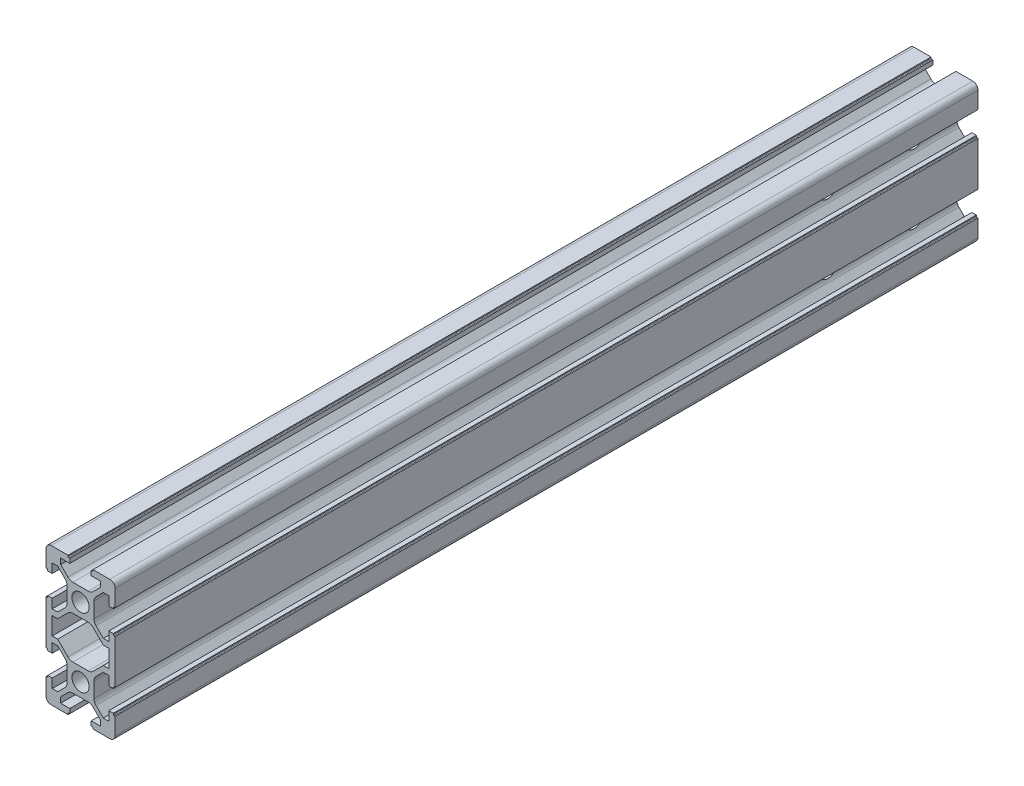
SolidWorks part; units mm, degrees
ref_plane "Alzado" through (0, 0, 0) normal (0, 0, 1) x (1, 0, 0)
ref_plane "Planta" through (0, 0, 0) normal (0, 1, 0) x (1, 0, 0)
ref_plane "Vista lateral" through (0, 0, 0) normal (1, 0, 0) x (0, 0, -1)
sketch "Croquis1" plane through (0, 0, 0) normal (0, 0, 1) x (1, 0, 0)
  line L0 (0, 0) -> (-10, -10) construction
  line L32 (0, 0) -> (-3.9, 0) construction
  line L58 (0, 0) -> (0, -3.9) construction
  line L60 (-4.4858, -3.6373) -> (-6.6, -5.7515)
  line L61 (-6.6, -5.7515) -> (-8.2, -5.7515)
  line L110 (-8.2, -5.7515) -> (-8.2, -3.1)
  line L111 (-8.2, -3.1) -> (-9.5, -3.1)
  line L112 (-9.5, -3.1) -> (-9.5, -3.4)
  line L113 (-9.7, -3.6) -> (-10, -3.6)
  line L114 (-10, -3.6) -> (-10, -8.5)
  line L115 (-3.6373, -4.4858) -> (-5.7515, -6.6)
  line L116 (-5.7515, -6.6) -> (-5.7515, -8.2)
  line L117 (-3.1, -8.2) -> (-3.1, -9.5)
  line L118 (-5.7515, -8.2) -> (-3.1, -8.2)
  line L119 (-3.1, -9.5) -> (-3.4, -9.5)
  line L120 (-3.6, -9.7) -> (-3.6, -10)
  line L121 (-3.6, -10) -> (-8.5, -10)
  line L122 (9.7, -3.6) -> (10, -3.6)
  line L123 (9.5, -3.1) -> (9.5, -3.4)
  line L124 (8.2, -3.1) -> (9.5, -3.1)
  line L125 (3.6, -10) -> (8.5, -10)
  line L126 (3.6, -9.7) -> (3.6, -10)
  line L127 (3.1, -9.5) -> (3.4, -9.5)
  line L128 (5.7515, -8.2) -> (3.1, -8.2)
  line L129 (3.1, -8.2) -> (3.1, -9.5)
  line L130 (5.7515, -6.6) -> (5.7515, -8.2)
  line L131 (3.6373, -4.4858) -> (5.7515, -6.6)
  line L132 (10, -3.6) -> (10, -8.5)
  line L133 (8.2, -5.7515) -> (8.2, -3.1)
  line L134 (6.6, -5.7515) -> (8.2, -5.7515)
  line L135 (4.4858, -3.6373) -> (6.6, -5.7515)
  line L136 (5.7515, 8.2) -> (3.1, 8.2)
  line L137 (3.6, 10) -> (8.5, 10)
  line L138 (-9.7, 3.6) -> (-10, 3.6)
  line L139 (-9.5, 3.1) -> (-9.5, 3.4)
  line L140 (-8.2, 3.1) -> (-9.5, 3.1)
  line L141 (-8.2, 5.7515) -> (-8.2, 3.1)
  line L142 (-6.6, 5.7515) -> (-8.2, 5.7515)
  line L143 (-4.4858, 3.6373) -> (-6.6, 5.7515)
  line L144 (3.1, 8.2) -> (3.1, 9.5)
  line L145 (3.1, 9.5) -> (3.4, 9.5)
  line L146 (3.6, 9.7) -> (3.6, 10)
  line L147 (-3.6, 10) -> (-8.5, 10)
  line L148 (-3.6, 9.7) -> (-3.6, 10)
  line L149 (-3.1, 9.5) -> (-3.4, 9.5)
  line L150 (-5.7515, 8.2) -> (-3.1, 8.2)
  line L151 (-3.1, 8.2) -> (-3.1, 9.5)
  line L152 (-5.7515, 6.6) -> (-5.7515, 8.2)
  line L153 (-3.6373, 4.4858) -> (-5.7515, 6.6)
  line L154 (-10, 3.6) -> (-10, 8.5)
  line L155 (4.4858, 3.6373) -> (6.6, 5.7515)
  line L156 (6.6, 5.7515) -> (8.2, 5.7515)
  line L157 (8.2, 5.7515) -> (8.2, 3.1)
  line L158 (10, 3.6) -> (10, 8.5)
  line L159 (3.6373, 4.4858) -> (5.7515, 6.6)
  line L160 (5.7515, 6.6) -> (5.7515, 8.2)
  line L161 (8.2, 3.1) -> (9.5, 3.1)
  line L162 (9.5, 3.1) -> (9.5, 3.4)
  line L163 (9.7, 3.6) -> (10, 3.6)
  line L164 (-3.9, 2.223) -> (-3.9, -2.223)
  line L165 (-2.223, -3.9) -> (2.223, -3.9)
  line L166 (3.9, -2.223) -> (3.9, 2.223)
  line L167 (2.223, 3.9) -> (-2.223, 3.9)
  circle A2 centre (0, 0) radius 2.5
  arc A3 (8.5, -10) -> (10, -8.5) centre (8.5, -8.5) ccw
  arc A4 (8.5, 10) -> (10, 8.5) centre (8.5, 8.5) cw
  arc A5 (-8.5, 10) -> (-10, 8.5) centre (-8.5, 8.5) ccw
  arc A6 (-10, -8.5) -> (-8.5, -10) centre (-8.5, -8.5) ccw
  arc A7 (-3.9, -2.223) -> (-4.4858, -3.6373) centre (-5.9, -2.223) cw
  arc A8 (4.4858, -3.6373) -> (3.9, -2.223) centre (5.9, -2.223) cw
  arc A9 (4.4858, 3.6373) -> (3.9, 2.223) centre (5.9, 2.223) ccw
  arc A10 (3.6373, 4.4858) -> (2.223, 3.9) centre (2.223, 5.9) cw
  arc A11 (-3.6373, 4.4858) -> (-2.223, 3.9) centre (-2.223, 5.9) ccw
  arc A12 (-4.4858, 3.6373) -> (-3.9, 2.223) centre (-5.9, 2.223) cw
  arc A13 (3.6373, -4.4858) -> (2.223, -3.9) centre (2.223, -5.9) ccw
  arc A14 (-3.6373, -4.4858) -> (-2.223, -3.9) centre (-2.223, -5.9) cw
  arc A15 (-3.4, -9.5) -> (-3.6, -9.7) centre (-3.4, -9.7) ccw
  arc A16 (3.6, -9.7) -> (3.4, -9.5) centre (3.4, -9.7) ccw
  arc A17 (9.7, -3.6) -> (9.5, -3.4) centre (9.7, -3.4) cw
  arc A18 (9.5, 3.4) -> (9.7, 3.6) centre (9.7, 3.4) cw
  arc A19 (3.4, 9.5) -> (3.6, 9.7) centre (3.4, 9.7) ccw
  arc A20 (-9.7, 3.6) -> (-9.5, 3.4) centre (-9.7, 3.4) cw
  arc A21 (-3.6, 9.7) -> (-3.4, 9.5) centre (-3.4, 9.7) ccw
  arc A22 (-9.5, -3.4) -> (-9.7, -3.6) centre (-9.7, -3.4) cw
  point P0 (0, 0)
  point P22 (10, -10)
  point P78 (10, 10)
  point P81 (-10, 10)
  point P90 (-3.9, -3.0515)
  point P93 (3.9, -3.0515)
  point P96 (3.9, 3.0515)
  point P99 (3.0515, 3.9)
  point P102 (-3.0515, 3.9)
  point P105 (-3.9, 3.0515)
  point P108 (3.0515, -3.9)
  point P111 (-3.0515, -3.9)
  point P116 (-3.6, -9.5)
  point P119 (3.6, -9.5)
  point P122 (9.5, -3.6)
  point P125 (9.5, 3.6)
  point P128 (3.6, 9.5)
  point P131 (-9.5, 3.6)
  point P134 (-3.6, 9.5)
  point P137 (-9.5, -3.6)
  dimension "D10" = 20
  dimension "D1" = 5
  dimension "D11" = 1.5
  dimension "D13" = 2
  dimension "D15" = 0.2
  dimension "D2" = 6.2
  dimension "D3" = 7.2
  dimension "D4" = 0.5
  dimension "D5" = 3.4
  dimension "D6" = 11.5029
  dimension "D7" = 6.1
  dimension "D8" = 1.8
  dimension "D9" = 1.2
extrude "Saliente-Extruir1" [suppressed] add sketch "Croquis1" along normal mid plane 100
sketch "Croquis3" plane through (0, 0, 0) normal (0, 0, 1) x (1, 0, 0)
  line L0 (-3.6363, -5.5152) -> (-6.6, -2.5556)
  line L3 (0, 0) -> (-10, 0) construction
  line L5 (-6.6, -2.5556) -> (-8.2, -2.5556)
  line L7 (0, -13.9) -> (0, -6.1) construction
  line L56 (-9.5, -13.1015) -> (-9.5, -13.4015)
  line L57 (-8.2, -13.1015) -> (-9.5, -13.1015)
  line L58 (-8.2, -15.7515) -> (-8.2, -13.1015)
  line L59 (-6.6, -15.7515) -> (-8.2, -15.7515)
  line L60 (-4.4858, -13.6373) -> (-6.6, -15.7515)
  line L61 (-3.9, -7.777) -> (-3.9, -12.223)
  line L62 (-6.6, -4.2515) -> (-4.4868, -6.3618)
  line L63 (-8.2, -4.2515) -> (-6.6, -4.2515)
  line L64 (-8.2, -6.9015) -> (-8.2, -4.2515)
  line L65 (-9.5, -6.9015) -> (-8.2, -6.9015)
  line L66 (-9.5, -6.6015) -> (-9.5, -6.9015)
  line L67 (-10, -6.4015) -> (-9.7, -6.4015)
  line L68 (-5.7515, -16.6) -> (-3.6373, -14.4858)
  line L69 (-5.7515, -18.2) -> (-5.7515, -16.6)
  line L70 (-3.1015, -18.2) -> (-5.7515, -18.2)
  line L71 (-3.1015, -19.5) -> (-3.1015, -18.2)
  line L72 (-3.4015, -19.5) -> (-3.1015, -19.5)
  line L73 (-3.6015, -20) -> (-3.6015, -19.7)
  line L74 (-8.5, -20) -> (-3.6015, -20)
  line L75 (-10, -13.6015) -> (-10, -18.5)
  line L76 (-9.7, -13.6015) -> (-10, -13.6015)
  line L102 (-10, -6.4015) -> (-10, 6.4015)
  line L103 (-8.2, -2.5556) -> (-8.2, 2.5556)
  line L104 (-2.223, -6.1) -> (2.223, -6.1)
  line L105 (-2.223, -13.9) -> (2.223, -13.9)
  line L106 (8.2, -2.5556) -> (8.2, 2.5556)
  line L107 (10, -6.4015) -> (10, 6.4015)
  line L108 (9.7, -13.6015) -> (10, -13.6015)
  line L109 (10, -13.6015) -> (10, -18.5)
  line L110 (8.5, -20) -> (3.6015, -20)
  line L111 (3.6015, -20) -> (3.6015, -19.7)
  line L112 (3.4015, -19.5) -> (3.1015, -19.5)
  line L113 (3.1015, -19.5) -> (3.1015, -18.2)
  line L114 (3.1015, -18.2) -> (5.7515, -18.2)
  line L115 (5.7515, -18.2) -> (5.7515, -16.6)
  line L116 (5.7515, -16.6) -> (3.6373, -14.4858)
  line L117 (10, -6.4015) -> (9.7, -6.4015)
  line L118 (9.5, -6.6015) -> (9.5, -6.9015)
  line L119 (9.5, -6.9015) -> (8.2, -6.9015)
  line L120 (8.2, -6.9015) -> (8.2, -4.2515)
  line L121 (8.2, -4.2515) -> (6.6, -4.2515)
  line L122 (6.6, -4.2515) -> (4.4868, -6.3618)
  line L123 (3.9, -7.777) -> (3.9, -12.223)
  line L124 (4.4858, -13.6373) -> (6.6, -15.7515)
  line L125 (6.6, -15.7515) -> (8.2, -15.7515)
  line L126 (8.2, -15.7515) -> (8.2, -13.1015)
  line L127 (8.2, -13.1015) -> (9.5, -13.1015)
  line L128 (9.5, -13.1015) -> (9.5, -13.4015)
  line L129 (6.6, -2.5556) -> (8.2, -2.5556)
  line L130 (3.6363, -5.5152) -> (6.6, -2.5556)
  line L131 (3.6363, 5.5152) -> (6.6, 2.5556)
  line L132 (6.6, 2.5556) -> (8.2, 2.5556)
  line L133 (9.5, 13.1015) -> (9.5, 13.4015)
  line L134 (8.2, 13.1015) -> (9.5, 13.1015)
  line L135 (8.2, 15.7515) -> (8.2, 13.1015)
  line L136 (6.6, 15.7515) -> (8.2, 15.7515)
  line L137 (4.4858, 13.6373) -> (6.6, 15.7515)
  line L138 (3.9, 7.777) -> (3.9, 12.223)
  line L139 (6.6, 4.2515) -> (4.4868, 6.3618)
  line L140 (8.2, 4.2515) -> (6.6, 4.2515)
  line L141 (8.2, 6.9015) -> (8.2, 4.2515)
  line L142 (9.5, 6.9015) -> (8.2, 6.9015)
  line L143 (9.5, 6.6015) -> (9.5, 6.9015)
  line L144 (10, 6.4015) -> (9.7, 6.4015)
  line L145 (5.7515, 16.6) -> (3.6373, 14.4858)
  line L146 (5.7515, 18.2) -> (5.7515, 16.6)
  line L147 (3.1015, 18.2) -> (5.7515, 18.2)
  line L148 (3.1015, 19.5) -> (3.1015, 18.2)
  line L149 (3.4015, 19.5) -> (3.1015, 19.5)
  line L150 (3.6015, 20) -> (3.6015, 19.7)
  line L151 (8.5, 20) -> (3.6015, 20)
  line L152 (10, 13.6015) -> (10, 18.5)
  line L153 (9.7, 13.6015) -> (10, 13.6015)
  line L154 (-2.223, 13.9) -> (2.223, 13.9)
  line L155 (-2.223, 6.1) -> (2.223, 6.1)
  line L156 (-9.7, 13.6015) -> (-10, 13.6015)
  line L157 (-10, 13.6015) -> (-10, 18.5)
  line L158 (-8.5, 20) -> (-3.6015, 20)
  line L159 (-3.6015, 20) -> (-3.6015, 19.7)
  line L160 (-3.4015, 19.5) -> (-3.1015, 19.5)
  line L161 (-3.1015, 19.5) -> (-3.1015, 18.2)
  line L162 (-3.1015, 18.2) -> (-5.7515, 18.2)
  line L163 (-5.7515, 18.2) -> (-5.7515, 16.6)
  line L164 (-5.7515, 16.6) -> (-3.6373, 14.4858)
  line L165 (-10, 6.4015) -> (-9.7, 6.4015)
  line L166 (-9.5, 6.6015) -> (-9.5, 6.9015)
  line L167 (-9.5, 6.9015) -> (-8.2, 6.9015)
  line L168 (-8.2, 6.9015) -> (-8.2, 4.2515)
  line L169 (-8.2, 4.2515) -> (-6.6, 4.2515)
  line L170 (-6.6, 4.2515) -> (-4.4868, 6.3618)
  line L171 (-3.9, 7.777) -> (-3.9, 12.223)
  line L172 (-4.4858, 13.6373) -> (-6.6, 15.7515)
  line L173 (-6.6, 15.7515) -> (-8.2, 15.7515)
  line L174 (-8.2, 15.7515) -> (-8.2, 13.1015)
  line L175 (-8.2, 13.1015) -> (-9.5, 13.1015)
  line L176 (-9.5, 13.1015) -> (-9.5, 13.4015)
  line L177 (-6.6, 2.5556) -> (-8.2, 2.5556)
  line L178 (-3.6363, 5.5152) -> (-6.6, 2.5556)
  line L179 (0, -10) -> (-9.5607, -19.5607) construction
  circle A8 centre (0, -10) radius 2.5
  arc A20 (-4.4858, -13.6373) -> (-3.9, -12.223) centre (-5.9, -12.223) ccw
  arc A21 (-3.9, -7.777) -> (-4.4868, -6.3618) centre (-5.9, -7.777) ccw
  arc A22 (-9.5, -6.6015) -> (-9.7, -6.4015) centre (-9.7, -6.6015) ccw
  arc A23 (-3.6363, -5.5152) -> (-2.223, -6.1) centre (-2.223, -4.1) ccw
  arc A24 (-2.223, -13.9) -> (-3.6373, -14.4858) centre (-2.223, -15.9) ccw
  arc A25 (-3.4015, -19.5) -> (-3.6015, -19.7) centre (-3.4015, -19.7) ccw
  arc A26 (-10, -18.5) -> (-8.5, -20) centre (-8.5, -18.5) ccw
  arc A27 (-9.7, -13.6015) -> (-9.5, -13.4015) centre (-9.7, -13.4015) ccw
  arc A34 (9.7, -13.6015) -> (9.5, -13.4015) centre (9.7, -13.4015) cw
  arc A35 (10, -18.5) -> (8.5, -20) centre (8.5, -18.5) cw
  arc A36 (3.4015, -19.5) -> (3.6015, -19.7) centre (3.4015, -19.7) cw
  arc A37 (2.223, -13.9) -> (3.6373, -14.4858) centre (2.223, -15.9) cw
  arc A38 (3.6363, -5.5152) -> (2.223, -6.1) centre (2.223, -4.1) cw
  arc A39 (9.5, -6.6015) -> (9.7, -6.4015) centre (9.7, -6.6015) cw
  arc A40 (3.9, -7.777) -> (4.4868, -6.3618) centre (5.9, -7.777) cw
  arc A41 (4.4858, -13.6373) -> (3.9, -12.223) centre (5.9, -12.223) cw
  arc A42 (4.4858, 13.6373) -> (3.9, 12.223) centre (5.9, 12.223) ccw
  arc A43 (3.9, 7.777) -> (4.4868, 6.3618) centre (5.9, 7.777) ccw
  arc A44 (9.5, 6.6015) -> (9.7, 6.4015) centre (9.7, 6.6015) ccw
  arc A45 (3.6363, 5.5152) -> (2.223, 6.1) centre (2.223, 4.1) ccw
  arc A46 (2.223, 13.9) -> (3.6373, 14.4858) centre (2.223, 15.9) ccw
  arc A47 (3.4015, 19.5) -> (3.6015, 19.7) centre (3.4015, 19.7) ccw
  arc A48 (10, 18.5) -> (8.5, 20) centre (8.5, 18.5) ccw
  arc A49 (9.7, 13.6015) -> (9.5, 13.4015) centre (9.7, 13.4015) ccw
  arc A50 (-9.7, 13.6015) -> (-9.5, 13.4015) centre (-9.7, 13.4015) cw
  arc A51 (-10, 18.5) -> (-8.5, 20) centre (-8.5, 18.5) cw
  arc A52 (-3.4015, 19.5) -> (-3.6015, 19.7) centre (-3.4015, 19.7) cw
  arc A53 (-2.223, 13.9) -> (-3.6373, 14.4858) centre (-2.223, 15.9) cw
  arc A54 (-3.6363, 5.5152) -> (-2.223, 6.1) centre (-2.223, 4.1) cw
  arc A55 (-9.5, 6.6015) -> (-9.7, 6.4015) centre (-9.7, 6.6015) cw
  arc A56 (-3.9, 7.777) -> (-4.4868, 6.3618) centre (-5.9, 7.777) cw
  arc A57 (-4.4858, 13.6373) -> (-3.9, 12.223) centre (-5.9, 12.223) cw
  circle A58 centre (0, 10) radius 2.5
  point P59 (8.2, 0)
  point P63 (8.2, 0)
  point P159 (10, 0)
  point P160 (-8.2, 0)
  point P174 (-8.2, 0)
  point P190 (-3.9, -10)
  point P193 (0, -10)
  dimension "D8" = 2
  dimension "D9" = 1.5
  dimension "D11" = 5
  dimension "D13" = 0.2
  dimension "D1" = 40
  dimension "D2" = 11.5
  dimension "D3" = 6.2
  dimension "D4" = 1.8
  dimension "D5" = 0.5
  dimension "D6" = 3.4
  dimension "D7" = 20
  dimension "D10" = 1.2
  dimension "D12" = 7.8
  dimension "D14" = 20
extrude "Saliente-Extruir3" add sketch "Croquis3" along normal mid plane 350 separate body
sketch "Sketch1" plane through (0, 20, 0) normal (0, 1, 0) x (1, 0, 0)
  line L0 (10, 175) -> (8.5, 175) construction
  line L1 (8.5, -175) -> (10, -175) construction
  line L2 (10, -175) -> (10, 175) construction
  line L3 (8.5, 175) -> (3.6015, 175) construction
  line L4 (3.6015, 175) -> (3.6015, -175) construction
  line L5 (3.6015, -175) -> (8.5, -175) construction
  line L6 (3.6373, 175) -> (2.223, 175) construction
  line L7 (2.223, -175) -> (3.6373, -175) construction
  line L8 (3.6373, -175) -> (3.6373, 175) construction
  line L10 (-2.223, -175) -> (2.223, -175) construction
  line L11 (-2.223, 175) -> (-3.6373, 175) construction
  line L12 (-3.6373, 175) -> (-3.6373, -175) construction
  line L13 (-3.6373, -175) -> (-2.223, -175) construction
  line L14 (-3.6015, 175) -> (-8.5, 175) construction
  line L15 (-8.5, -175) -> (-3.6015, -175) construction
  line L16 (-3.6015, -175) -> (-3.6015, 175) construction
  line L17 (-8.5, 175) -> (-10, 175) construction
  line L18 (-10, 175) -> (-10, -175) construction
  line L19 (-10, -175) -> (-8.5, -175) construction
  line L20 (10, 175) -> (8.5, 175)
  line L21 (8.5, -175) -> (10, -175)
  line L22 (10, -175) -> (10, -75)
  line L23 (3.6373, 175) -> (3.6015, 175)
  line L24 (3.6015, -75) -> (3.6015, -175)
  line L25 (3.6015, -175) -> (8.5, -175)
  line L26 (3.6373, 175) -> (2.223, 175)
  line L27 (2.223, -175) -> (3.6373, -175)
  line L28 (3.6373, -175) -> (3.6373, -75)
  line L30 (-2.223, -175) -> (2.223, -175)
  line L31 (-3.6015, 175) -> (-3.6373, 175)
  line L32 (-3.6373, -75) -> (-3.6373, -175)
  line L33 (-3.6373, -175) -> (-2.223, -175)
  line L34 (-3.6015, 175) -> (-3.6373, 175)
  line L35 (-8.5, -175) -> (-3.6015, -175)
  line L36 (-3.6015, -175) -> (-3.6015, -75)
  line L37 (-8.5, 175) -> (-10, 175)
  line L38 (-10, -75) -> (-10, -175)
  line L39 (-10, -175) -> (-8.5, -175)
  line L40 (-10, -75) -> (10, -75)
  line L41 (10, -75) -> (10, -175)
  line L42 (10, -175) -> (8.5, -175)
  line L43 (10, -175) -> (-10, -175)
  line L44 (-10, -175) -> (-10, -75)
  dimension "D1" = 350
  dimension "D2" = 100
extrude "Cut-Extrude3" cut sketch "Sketch1" against normal blind 90
sketch "Sketch2" plane through (10, 0, 0) normal (1, 0, 0) x (0, 0, -1)
  line L8 (-75, 6.4015) -> (-75, -6.4015) construction
  line L9 (-75, -6.4015) -> (175, -6.4015) construction
  line L10 (175, -6.4015) -> (175, 6.4015) construction
  line L11 (175, 6.4015) -> (-75, 6.4015) construction
  line L12 (-75, 20) -> (-75, 18.5)
  line L14 (175, 18.5) -> (175, 20)
  line L16 (-75, -18.5) -> (-75, -20)
  line L18 (175, -20) -> (175, -18.5)
  line L20 (-75, 6.4015) -> (-75, -6.4015)
  line L21 (-75, -6.4015) -> (175, -6.4015)
  line L22 (175, -6.4015) -> (175, 6.4015)
  line L23 (175, 6.4015) -> (-75, 6.4015)
  line L24 (-75, 18.5) -> (-75, -18.2)
  line L25 (175, 18.5) -> (175, -18.5)
  line L26 (125, 20) -> (125, -20)
  line L27 (125, 0) -> (175, 0) construction
  line L28 (125, -20) -> (175, -20)
  line L29 (150, 20) -> (150, -20) construction
  line L30 (-75, 18.5) -> (175, 18.5) construction
  line L31 (-75, 20) -> (175, 20) construction
  line L32 (-75, 18.5) -> (175, 18.5)
  line L33 (-75, 20) -> (175, 20)
  line L34 (-75, -20) -> (175, -20) construction
  line L35 (-75, -18.5) -> (175, -18.5) construction
  line L36 (-75, -20) -> (175, -20)
  line L37 (-75, -18.5) -> (175, -18.5)
  circle A0 centre (137.5, 10) radius 3
  circle A1 centre (162.5, 10) radius 3
  circle A2 centre (162.5, -10) radius 3
  circle A3 centre (137.5, -10) radius 3
  point P21 (137.5, 10)
  point P23 (162.5, 10)
  point P25 (162.5, -10)
  point P27 (137.5, -10)
  dimension "D3" = 6
  dimension "D1" = 50
  dimension "D2" = 25
  dimension "D5" = 12.5
  dimension "D6" = 250
hole_wizard "Ø6.0mm Dowel Hole1" positions "Sketch2" profile "Sketch4" hole size "Ø6.0" standard "ANSI Metric" end condition through all
sketch "Sketch4" plane through (10, -10, -137.5) normal (0, 1, 0) x (0, 0, -1)
  line L0 (0, 0) -> (0, 20)
  line L1 (0, 20) -> (3, 20)
  line L2 (3, 20) -> (3, 0)
  line L5 (3, 0) -> (0, 0)
  line L11 (0, -6.35) -> (0, 107.95) construction
  dimension "Thru Hole Dia." = 6
  dimension "Thru Hole Depth" = 20
sketch "Sketch5" [suppressed] plane through (0, -10, 0) normal (0, -1, 0) x (1, 0, 0)
  line L0 (-10, -175) -> (-8.5, -175) construction
  line L1 (-8.5, -175) -> (-3.6, -175) construction
  line L2 (-3.6373, -175) -> (-2.223, -175) construction
  line L3 (2.223, -175) -> (3.6373, -175) construction
  line L4 (-2.223, -175) -> (2.223, -175) construction
  line L5 (8.5, -175) -> (10, -175) construction
  line L6 (3.6, -175) -> (8.5, -175) construction
  line L7 (-10, -175) -> (-8.5, -175)
  line L8 (-8.5, -175) -> (-3.6, -175)
  line L9 (-3.6373, -175) -> (-2.223, -175)
  line L10 (2.223, -175) -> (3.6373, -175)
  line L11 (-2.223, -175) -> (2.223, -175)
  line L12 (8.5, -175) -> (10, -175)
  line L13 (3.6, -175) -> (8.5, -175)
  line L14 (10, -175) -> (17.5978, -75)
  line L15 (17.5978, -75) -> (-16.0216, -75)
  line L16 (-16.0216, -75) -> (-10, -175)
  line L17 (-10, -175) -> (10, -175)
  dimension "D1" = 250
extrude "Cut-Extrude4" [suppressed] cut sketch "Sketch5" against normal through all
